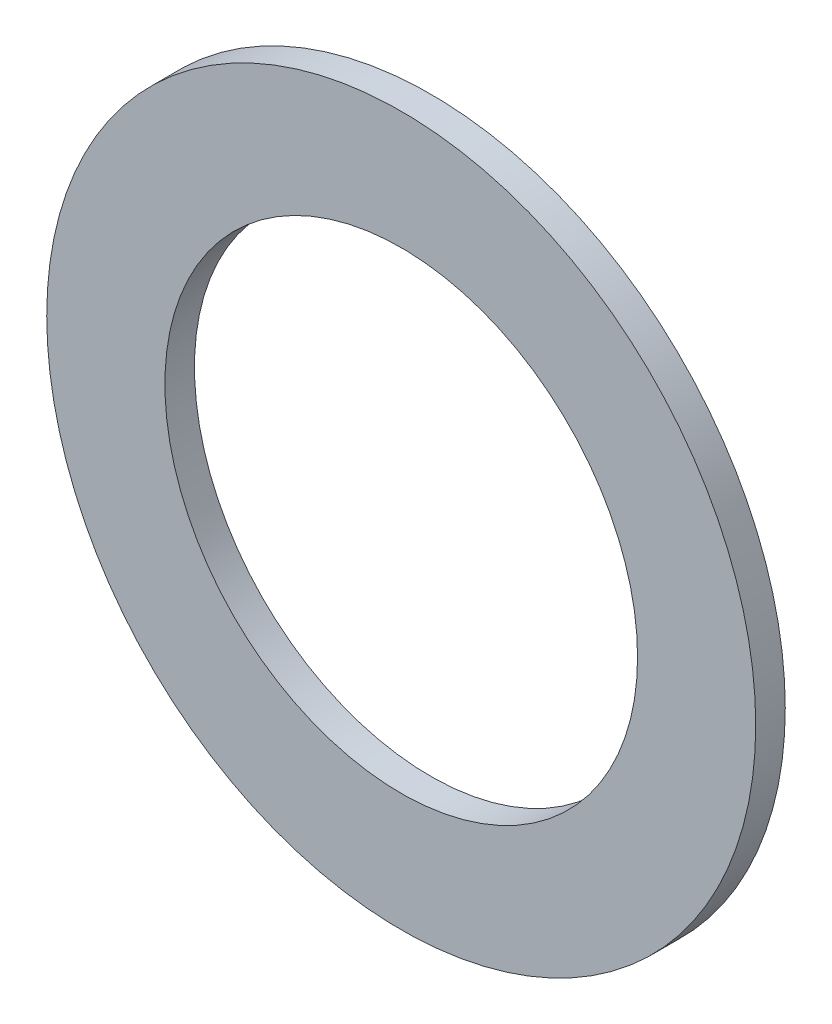
SolidWorks part; units mm, degrees
ref_plane "Plan de face" through (0, 0, 0) normal (0, 0, 1) x (1, 0, 0)
ref_plane "Plan de dessus" through (0, 0, 0) normal (0, 1, 0) x (1, 0, 0)
ref_plane "Plan de droite" through (0, 0, 0) normal (1, 0, 0) x (0, 0, -1)
sketch "Esquisse1" plane through (0, 0, 0) normal (0, 0, 1) x (1, 0, 0)
  circle A0 centre (0, 0) radius 76.2
  circle A1 centre (0, 0) radius 50.8
  dimension "D1" = 152.4
  dimension "D2" = 101.6
extrude "Boss.-Extru.1" add sketch "Esquisse1" along normal blind 6.35
